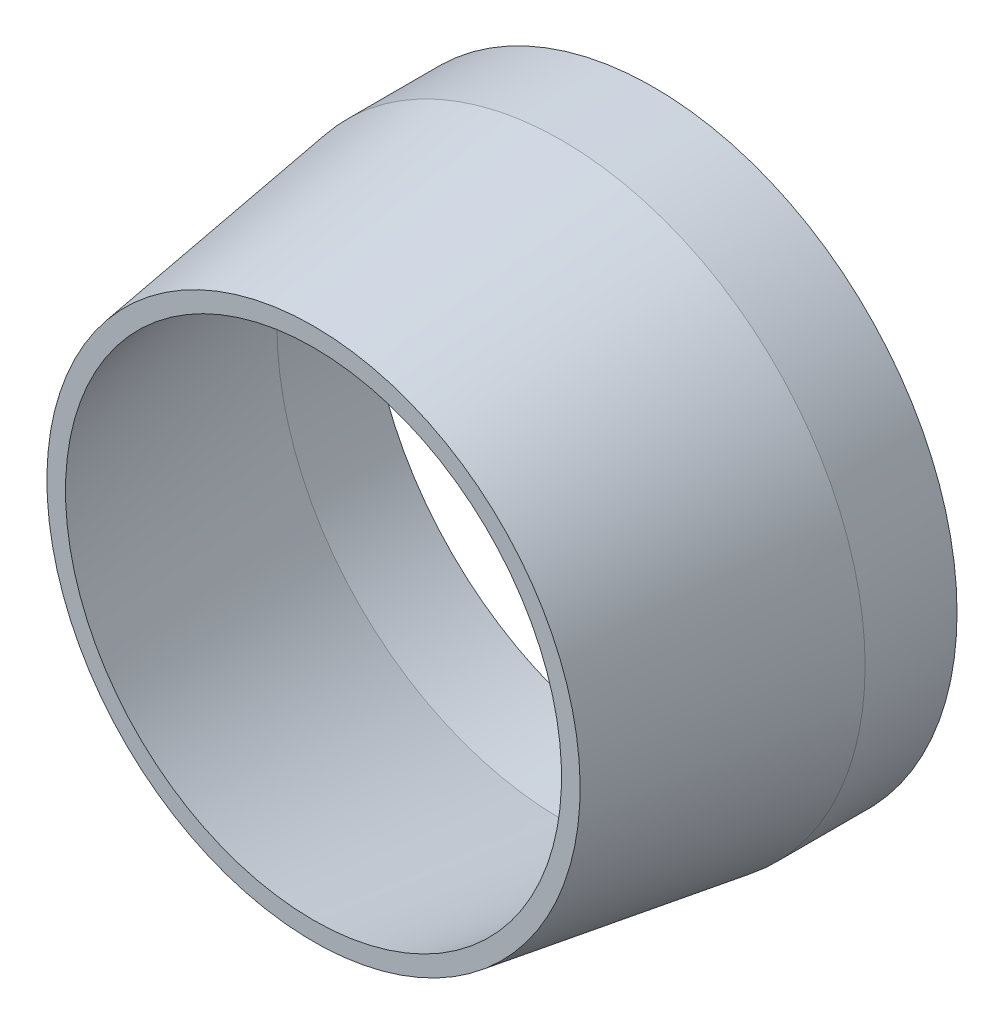
SolidWorks part; units mm, degrees
ref_plane "Piano frontale" through (0, 0, 0) normal (0, 0, 1) x (1, 0, 0)
ref_plane "Piano superiore" through (0, 0, 0) normal (0, 1, 0) x (1, 0, 0)
ref_plane "Piano destro" through (0, 0, 0) normal (1, 0, 0) x (0, 0, -1)
sketch "Schizzo1" plane through (0, 0, 0) normal (0, 0, 1) x (1, 0, 0)
  circle A0 centre (0, 0) radius 3300
  circle A1 centre (0, 0) radius 3100
  dimension "D1" = 200
  dimension "D2" = 6600
extrude "Estrusione-Estrusione1" add sketch "Schizzo1" along normal blind 1000
sketch "Schizzo3" plane through (0, 0, 0) normal (1, 0, 0) x (0, 0, -1)
  line L0 (-3700, 2697.8171) -> (-3700, 2900)
  line L1 (-3700, 2900) -> (-1000, 3300)
  line L2 (-1000, 3300) -> (-1000, 3097.8171)
  line L5 (-1000, 0) -> (-3700, 0)
  line L6 (-3700, 2697.8171) -> (-1000, 3097.8171)
  line L15 (-1000, 3300) -> (-1000, -3300) construction
  dimension "D1" = 2700
  dimension "D2" = 2900
revolve "Rivoluzione1" add sketch "Schizzo3" angle 360 about L5
